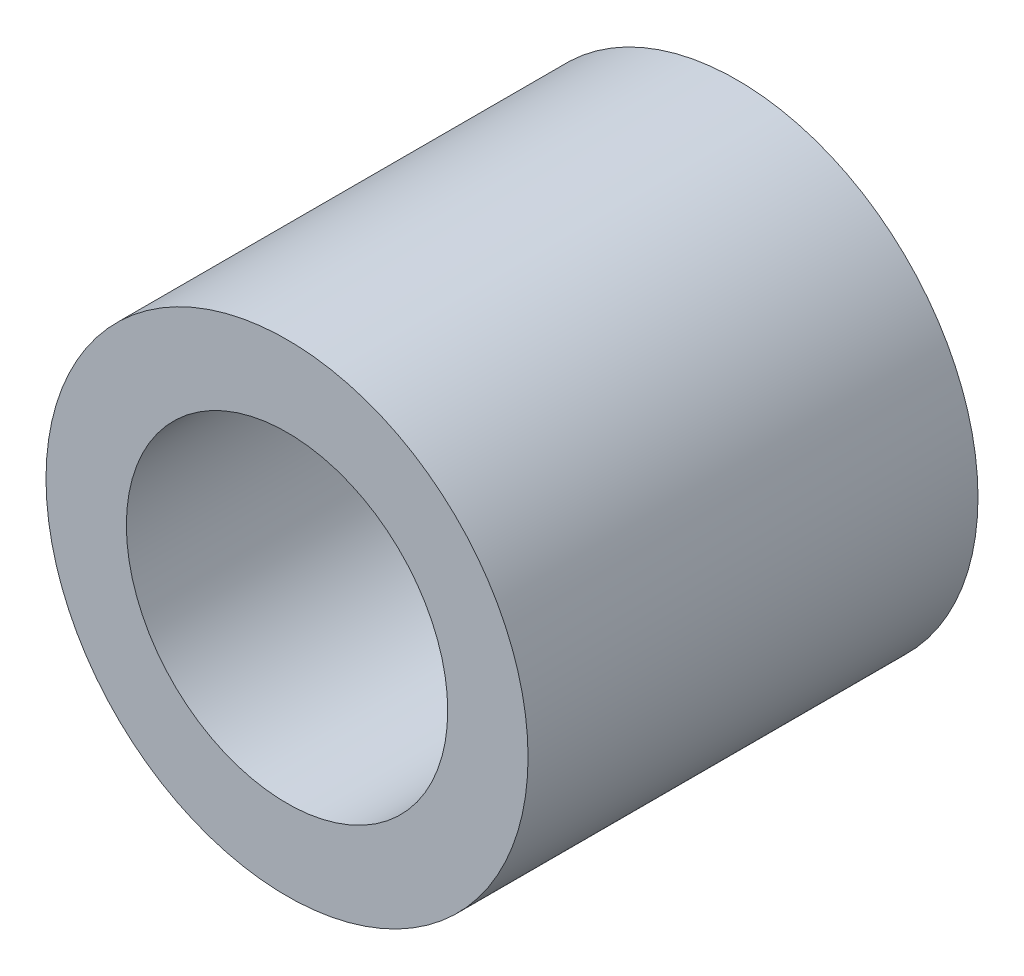
SolidWorks part; units mm, degrees
ref_plane "Front Plane" through (0, 0, 0) normal (0, 0, 1) x (1, 0, 0)
ref_plane "Top Plane" through (0, 0, 0) normal (0, 1, 0) x (1, 0, 0)
ref_plane "Right Plane" through (0, 0, 0) normal (1, 0, 0) x (0, 0, -1)
sketch "Sketch1" plane through (0, 0, 0) normal (0, 0, 1) x (1, 0, 0)
  circle A0 centre (0, 0) radius 3.75
  dimension "D1" = 7.5
extrude "Boss-Extrude1" add sketch "Sketch1" along normal blind 7
sketch "Sketch2" plane through (0, 0, 7) normal (0, 0, 1) x (1, 0, 0)
  circle A0 centre (0, 0) radius 2.5
  dimension "D1" = 5
extrude "Cut-Extrude1" cut sketch "Sketch2" against normal blind 5
